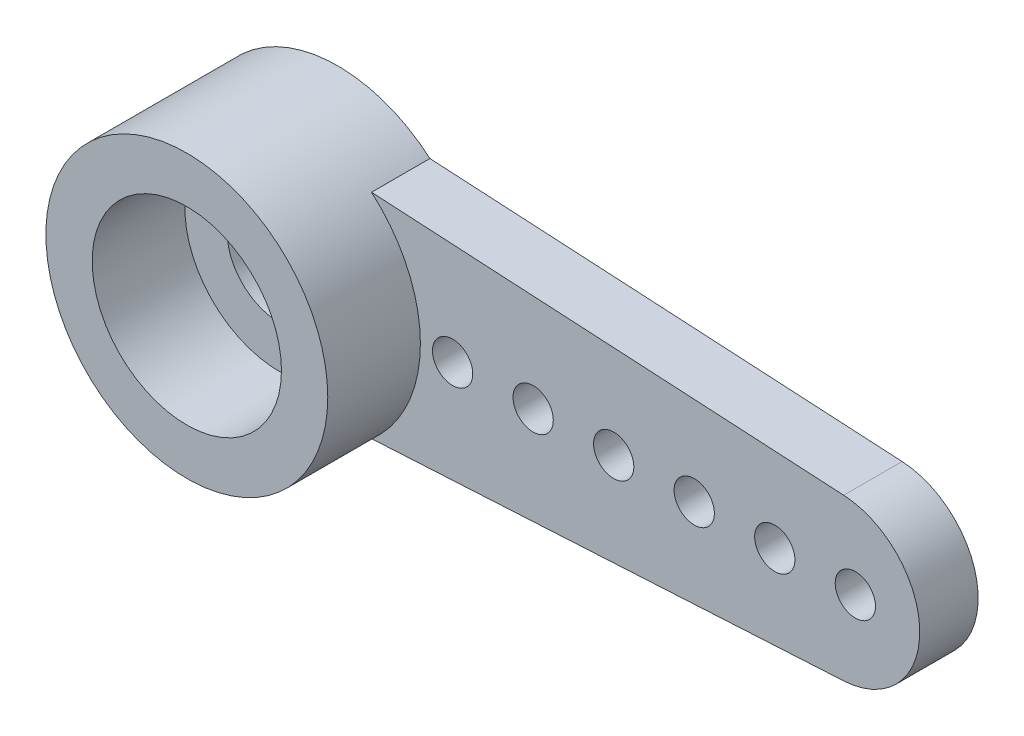
SolidWorks part; units mm, degrees
material "ABS"
ref_plane "前视基准面" through (0, 0, 0) normal (0, 0, 1) x (1, 0, 0)
ref_plane "上视基准面" through (0, 0, 0) normal (0, 1, 0) x (1, 0, 0)
ref_plane "右视基准面" through (0, 0, 0) normal (1, 0, 0) x (0, 0, -1)
other "Configuration Table"
sketch "草图1" plane through (0, 0, 0) normal (0, 0, 1) x (1, 0, 0)
  line L0 (-4.8051, 3.045) -> (16.8893, 1.8366)
  line L1 (-3.5, 8.2939) -> (-3.5, -8.5966) construction
  line L2 (16.2041, -1.8748) -> (-5.5978, -3.0892)
  line L3 (15.9, 7.2301) -> (15.9, -7.2734) construction
  line L4 (2.2864, 6.2453) -> (2.2864, -4.4515) construction
  circle A0 centre (13.9, 0) radius 2
  circle A1 centre (0, 0) radius 2.7731
  circle A2 centre (0, 0) radius 3.5
  point P14 (2.2864, -2.65)
  point P15 (2.2864, 2.65)
  dimension "D2" = 7
  dimension "D3" = 4
  dimension "D1" = 19.4
  dimension "D4" = 5.3
extrude "凸台-拉伸1" add sketch "草图1" along normal blind 1.45 contours L2 A2 L0 A1 | A1 | L0 A2 L2 A1 | L0 A2 | L2 A2 | A2 L2 A0 L0 | A0 A2
sketch "草图2" plane through (0, 0, 1.45) normal (0, 0, 1) x (1, 0, 0)
  circle A1 centre (0, 0) radius 2.35
  circle A2 centre (0, 0) radius 3.5
  arc A3 (2.2864, 2.65) -> (2.2864, -2.65) centre (0, 0) ccw construction
  dimension "D1" = 4.7
extrude "凸台-拉伸2" add sketch "草图2" along normal blind 2.3
sketch "草图3" plane through (0, 0, 0) normal (0, 0, -1) x (-1, 0, 0)
  circle A0 centre (0, 0) radius 2.3
  dimension "D1" = 4.6
extrude "切除-拉伸1" cut sketch "草图3" against normal blind 0.7
sketch "草图4" plane through (0, 0, 0.7) normal (0, 0, -1) x (-1, 0, 0)
  circle A0 centre (0, 0) radius 1.3
  dimension "D1" = 2.6
extrude "切除-拉伸2" cut sketch "草图4" against normal through all
sketch "草图5" plane through (0, 0, 0) normal (0, 0, -1) x (-1, 0, 0)
  line L0 (-15.9, 4.7285) -> (-15.9, -4.2754) construction
  line L1 (-14.8, 4.1484) -> (-14.8, -4.5312) construction
  arc A1 (-14.0112, 1.9969) -> (-14.0112, -1.9969) centre (-13.9, 0) ccw construction
  circle A2 centre (-14.3, 0) radius 0.5
  dimension "D1" = 1
  dimension "D2" = 1.1
extrude "切除-拉伸3" cut sketch "草图5" against normal through all contours A2
pattern_linear "阵列(线性)1" count 6 spacing 2 along (-1, 0, 0) of "切除-拉伸3"
